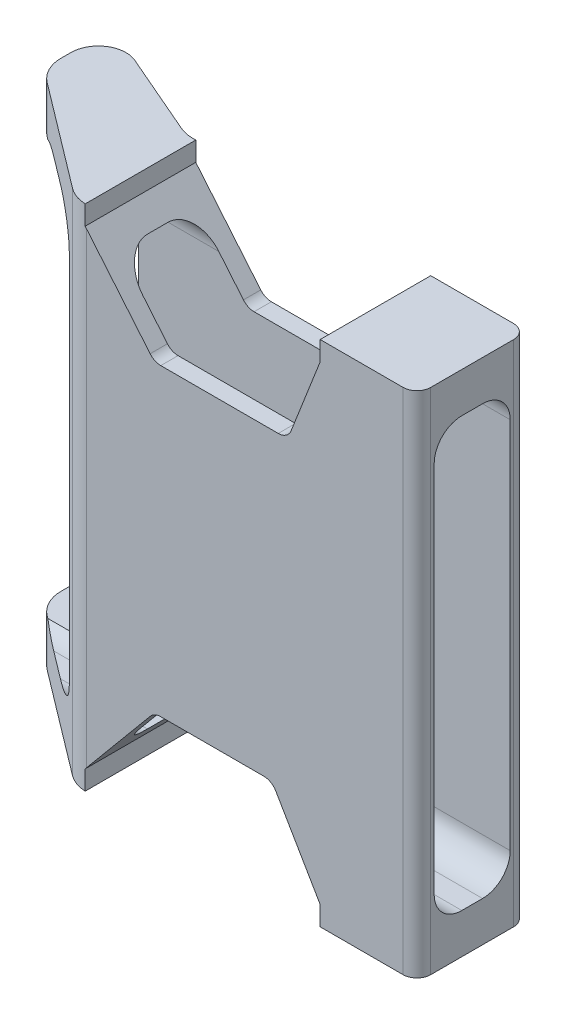
SolidWorks part; units mm, degrees
material "ABS"
ref_plane "Front Plane" through (0, 0, 0) normal (0, 0, 1) x (1, 0, 0)
ref_plane "Top Plane" through (0, 0, 0) normal (0, 1, 0) x (1, 0, 0)
ref_plane "Right Plane" through (0, 0, 0) normal (1, 0, 0) x (0, 0, -1)
sketch "Sketch1" plane through (0, 0, 0) normal (0, 1, 0) x (1, 0, 0)
  line L1 (0, -6) -> (34, -6)
  line L2 (0, -6) -> (0, 6)
  line L3 (0, 6) -> (34, 6)
  line L4 (34, -6) -> (34, 6)
  point P4 (0, 0)
  dimension "D1" = 12
  dimension "D2" = 34
extrude "Boss-Extrude1" add sketch "Sketch1" along normal blind 34
sketch "Sketch2" plane through (0, 0, 0) normal (0, -1, 0) x (1, 0, 0)
  line L0 (8.7675, -2.2086) -> (2.7938, -4.7919)
  line L1 (33, 6) -> (10.1028, 6)
  line L2 (34, 5) -> (34, -1)
  line L3 (33, -2) -> (9.7757, -2)
  line L5 (0, -2.9561) -> (0, -2.2632)
  line L6 (0, -6) -> (0, 6) construction
  line L7 (1.0073, -0.2378) -> (8.57, 5.4854)
  arc A0 (9.7757, -2) -> (8.7675, -2.2086) centre (9.7757, -4.54) ccw
  arc A1 (10.1028, 6) -> (8.57, 5.4854) centre (10.1028, 3.46) ccw
  arc A2 (0, -2.2632) -> (1.0073, -0.2378) centre (2.54, -2.2632) cw
  arc A3 (2.7938, -4.7919) -> (0, -2.9561) centre (2, -2.9561) cw
  arc A4 (33, 6) -> (34, 5) centre (33, 5) cw
  arc A5 (34, -1) -> (33, -2) centre (33, -1) cw
  point P12 (9.25, -2)
  point P15 (9.25, 6)
  point P18 (0, -1)
  point P21 (0, -6)
  point P24 (34, 6)
  point P27 (34, -2)
  dimension "D4" = 2.54
  dimension "D5" = 2
  dimension "D6" = 1
  dimension "D1" = 8
  dimension "D2" = 24.75
  dimension "D3" = 5
extrude "Cut-Extrude-Thin1" cut sketch "Sketch2" against normal through all thin
sketch "Sketch3" plane through (0.4812, 0, -0.6359) normal (-0.6034, 0, 0.7974) x (0.7974, 0, 0.6034)
  line L0 (-2.1891, 34) -> (-2.1891, 0) construction
  line L1 (-2.1891, 32) -> (7.3109, 32)
  line L2 (-2.1891, 32) -> (-2.1891, 2)
  line L3 (-2.1891, 2) -> (7.3109, 2)
  line L4 (8.3109, 31) -> (8.3109, 3)
  line L5 (10.1439, 34) -> (0.6597, 34) construction
  line L6 (10.1439, 0) -> (0.6597, 0) construction
  arc A0 (7.3109, 2) -> (8.3109, 3) centre (7.3109, 3) ccw
  arc A1 (7.3109, 32) -> (8.3109, 31) centre (7.3109, 31) cw
  point P14 (8.3109, 32)
  dimension "D4" = 1
  dimension "D1" = 10.5
  dimension "D2" = 2
  dimension "D3" = 2
extrude "Cut-Extrude1" cut sketch "Sketch3" against normal blind 2
sketch "Sketch5" plane through (2.1858, 0, -5.0548) normal (0.3969, 0, -0.9179) x (-0.9179, 0, -0.3969)
  line L0 (1.3376, 0) -> (1.3376, 34) construction
  line L1 (1.3376, 32) -> (-7.1707, 32)
  line L2 (1.3376, 32) -> (1.3376, 2)
  line L3 (1.3376, 2) -> (-7.1707, 2)
  line L4 (-7.1707, 32) -> (-7.1707, 2)
  line L5 (-7.1707, 34) -> (-7.1707, 0) construction
  line L6 (-0.6624, 34) -> (-7.1707, 34) construction
  line L7 (-0.6624, 0) -> (-7.1707, 0) construction
  dimension "D1" = 2
  dimension "D2" = 2
extrude "Cut-Extrude2" cut sketch "Sketch5" against normal blind 1
sketch "Sketch6" plane through (0, 0, 6) normal (0, 0, 1) x (1, 0, 0)
  line L0 (7.5179, 32) -> (0.0644, 32) construction
  line L1 (5.1084, 32) -> (6.1084, 32)
  line L2 (4.1084, 31) -> (4.1084, 3)
  line L3 (5.1084, 2) -> (6.1084, 2)
  line L4 (7.1084, 31) -> (7.1084, 3)
  line L5 (10, 34) -> (27, 34)
  line L6 (10.1028, 34) -> (33, 34) construction
  line L7 (27, 34) -> (24.8995, 28.6354)
  line L8 (23.9684, 28) -> (15.4684, 28)
  line L9 (14.7002, 28.3598) -> (10, 34)
  line L11 (10, 0) -> (14.7002, 5.6402)
  line L16 (10.1028, 0) -> (33, 0) construction
  line L17 (15.4684, 6) -> (22.9256, 6)
  line L18 (23.7894, 5.5039) -> (27, 0)
  line L19 (27, 0) -> (10, 0)
  arc A0 (4.1084, 3) -> (5.1084, 2) centre (5.1084, 3) ccw
  arc A1 (6.1084, 2) -> (7.1084, 3) centre (6.1084, 3) ccw
  arc A2 (6.1084, 32) -> (7.1084, 31) centre (6.1084, 31) cw
  arc A3 (5.1084, 32) -> (4.1084, 31) centre (5.1084, 31) ccw
  arc A4 (24.8995, 28.6354) -> (23.9684, 28) centre (23.9684, 29) cw
  arc A5 (15.4684, 28) -> (14.7002, 28.3598) centre (15.4684, 29) cw
  arc A6 (22.9256, 6) -> (23.7894, 5.5039) centre (22.9256, 5) cw
  arc A7 (14.7002, 5.6402) -> (15.4684, 6) centre (15.4684, 5) cw
  point P11 (7.1084, 2)
  point P14 (7.1084, 32)
  point P17 (4.1084, 32)
  point P36 (24.6508, 28)
  point P39 (15, 28)
  point P40 (23.5, 6)
  point P45 (15, 6)
  dimension "D2" = 1
  dimension "D8" = 1
  dimension "D14" = 1
  dimension "D1" = 3
  dimension "D3" = 17
  dimension "D4" = 7
  dimension "D5" = 5
  dimension "D6" = 5
  dimension "D7" = 6
  dimension "D9" = 6
  dimension "D10" = 17
  dimension "D11" = 8.5
  dimension "D12" = 7
  dimension "D13" = 8.5
extrude "Cut-Extrude3" cut sketch "Sketch6" against normal through all
sketch "Sketch7" plane through (34, 0, 0) normal (1, 0, 0) x (0, 0, -1)
  line L0 (-6, 34) -> (-6, 0) construction
  line L1 (-2.75, 32.5) -> (-1.25, 32.5)
  line L2 (-4.75, 30.5) -> (-4.75, 3.5)
  line L3 (-2.75, 1.5) -> (-1.25, 1.5)
  line L4 (0.75, 30.5) -> (0.75, 3.5)
  line L6 (2, 34) -> (2, 0) construction
  line L7 (-5, 34) -> (1, 34) construction
  line L8 (-5, 0) -> (1, 0) construction
  arc A0 (-4.75, 3.5) -> (-2.75, 1.5) centre (-2.75, 3.5) ccw
  arc A1 (-1.25, 1.5) -> (0.75, 3.5) centre (-1.25, 3.5) ccw
  arc A2 (-1.25, 32.5) -> (0.75, 30.5) centre (-1.25, 30.5) cw
  arc A3 (-2.75, 32.5) -> (-4.75, 30.5) centre (-2.75, 30.5) ccw
  dimension "D5" = 2
  dimension "D1" = 1.25
  dimension "D2" = 1.25
  dimension "D3" = 1.5
  dimension "D4" = 1.5
extrude "Cut-Extrude4" cut sketch "Sketch7" against normal through all
sketch "Sketch8" plane through (0, 0, 0) normal (0, -1, 0) x (1, 0, 0)
  line L4 (27, 6) -> (27, -2)
  line L5 (27, -2) -> (33, -2)
  line L6 (34, -1) -> (34, 5)
  line L7 (33, 6) -> (27, 6)
  line L8 (27, 6) -> (27, -2)
  line L9 (27, -2) -> (33, -2)
  line L10 (34, -1) -> (34, 5)
  line L11 (33, 6) -> (27, 6)
  line L13 (10, -2) -> (10, 5.9979)
  line L14 (8.57, 5.4854) -> (1.0073, -0.2378)
  line L15 (0, -2.2632) -> (0, -2.9561)
  line L16 (2.7938, -4.7919) -> (8.7675, -2.2086)
  line L17 (9.7757, -2) -> (10, -2)
  line L18 (10, -2) -> (10, 5.9979)
  line L19 (8.57, 5.4854) -> (1.0073, -0.2378)
  line L20 (0, -2.2632) -> (0, -2.9561)
  line L21 (2.7938, -4.7919) -> (8.7675, -2.2086)
  line L22 (9.7757, -2) -> (10, -2)
  arc A2 (33, -2) -> (34, -1) centre (33, -1) ccw
  arc A3 (34, 5) -> (33, 6) centre (33, 5) ccw
  arc A4 (33, -2) -> (34, -1) centre (33, -1) ccw
  arc A5 (34, 5) -> (33, 6) centre (33, 5) ccw
  arc A8 (10, 5.9979) -> (8.57, 5.4854) centre (10.1028, 3.46) ccw
  arc A9 (1.0073, -0.2378) -> (0, -2.2632) centre (2.54, -2.2632) ccw
  arc A10 (0, -2.9561) -> (2.7938, -4.7919) centre (2, -2.9561) ccw
  arc A11 (9.7757, -2) -> (8.7675, -2.2086) centre (9.7757, -4.54) ccw
  arc A12 (10, 5.9979) -> (8.57, 5.4854) centre (10.1028, 3.46) ccw
  arc A13 (1.0073, -0.2378) -> (0, -2.2632) centre (2.54, -2.2632) ccw
  arc A14 (0, -2.9561) -> (2.7938, -4.7919) centre (2, -2.9561) ccw
  arc A15 (9.7757, -2) -> (8.7675, -2.2086) centre (9.7757, -4.54) ccw
  dimension "D1" = 0
  dimension "D2" = 0
extrude "Boss-Extrude2" add sketch "Sketch8" along normal blind 1.4
ref_plane "Plane1" through (0, 17, 0) normal (0, -1, 0) x (-1, 0, 0)
mirror "Mirror1" about plane through (0, 17, 0) normal (0, -1, 0) of "Boss-Extrude2"
